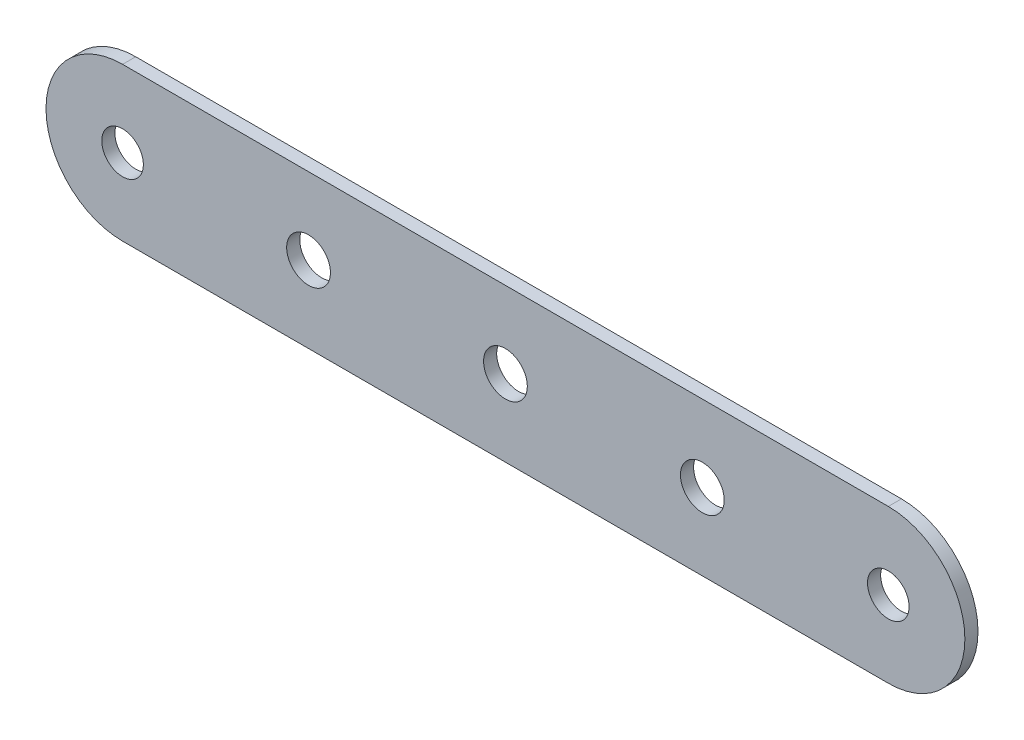
SolidWorks part; units mm, degrees
material "Mahogany"
ref_plane "Front Plane" through (0, 0, 0) normal (0, 0, 1) x (1, 0, 0)
ref_plane "Top Plane" through (0, 0, 0) normal (0, 1, 0) x (1, 0, 0)
ref_plane "Right Plane" through (0, 0, 0) normal (1, 0, 0) x (0, 0, -1)
sketch "Sketch1" plane through (0, 0, 0) normal (0, 0, 1) x (1, 0, 0)
  line L0 (-35.5297, 2.1311) -> (314.4703, 2.1311) construction
  line L1 (-35.5297, 37.1311) -> (314.4703, 37.1311)
  line L2 (-35.5297, -32.8689) -> (314.4703, -32.8689)
  line L3 (139.4703, -70.1329) -> (139.4703, 64.3952) construction
  arc A0 (-35.5297, 37.1311) -> (-35.5297, -32.8689) centre (-35.5297, 2.1311) ccw
  arc A1 (314.4703, -32.8689) -> (314.4703, 37.1311) centre (314.4703, 2.1311) ccw
  circle A2 centre (-35.5297, 2.1311) radius 9.5
  circle A3 centre (314.4703, 2.1311) radius 9.5
  circle A4 centre (139.4703, 2.1311) radius 10
  circle A5 centre (229.4703, 2.1311) radius 10
  circle A6 centre (49.4703, 2.1311) radius 10
  point P3 (139.4703, 2.1311)
  point P22 (32.5649, 2.1311)
  dimension "D9" = 19
  dimension "D10" = 19
  dimension "D2" = 2
  dimension "D3" = 175
  dimension "D4" = 2
  dimension "D8" = 70
  dimension "D12" = 175
extrude "Boss-Extrude1" add sketch "Sketch1" along normal blind 6
